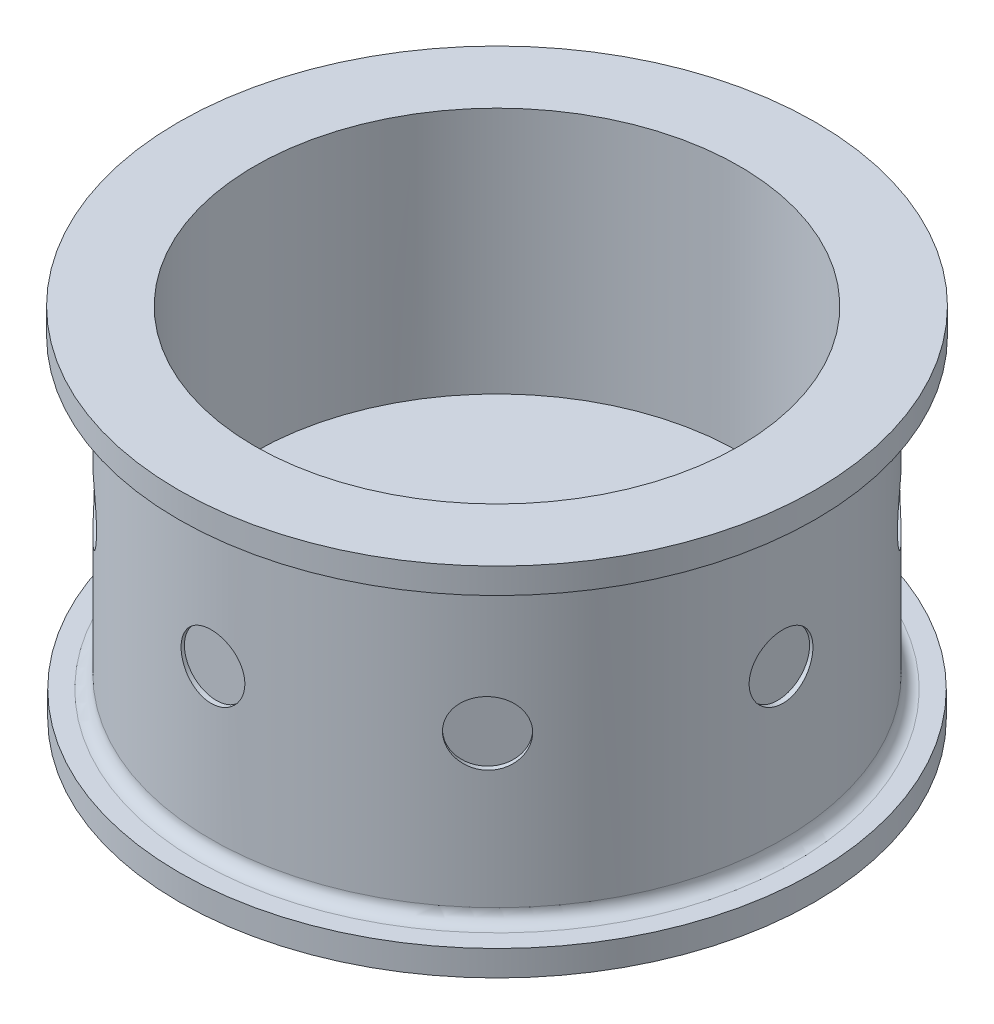
SolidWorks part; units mm, degrees
ref_plane "Alzado" through (0, 0, 0) normal (0, 0, 1) x (1, 0, 0)
ref_plane "Planta" through (0, 0, 0) normal (0, 1, 0) x (1, 0, 0)
ref_plane "Vista lateral" through (0, 0, 0) normal (1, 0, 0) x (0, 0, -1)
sketch "Sketch1" plane through (0, 0, 0) normal (0, 1, 0) x (1, 0, 0)
  circle A0 centre (0, 0) radius 19
  circle A1 centre (0, 0) radius 22.4
  dimension "D1" = 38
  dimension "D2" = 3.4
extrude "Boss-Extrude1" add sketch "Sketch1" along normal blind 28
sketch "Sketch2" plane through (0, 0, 0) normal (0, -1, 0) x (1, 0, 0)
  line L1 (-22.4, 0) -> (0, 0)
  line L2 (0, 0) -> (22.4, 0)
  arc A1 (-22.4, 0) -> (22.4, 0) centre (0, 0) ccw
  dimension "D1" = 22.4
extrude "Boss-Extrude2" add sketch "Sketch2" against normal blind 8.6
sketch "Sketch3" plane through (0, 0, 0) normal (0, -1, 0) x (-1, 0, 0)
  circle A0 centre (0, 0) radius 4
  dimension "D1" = 8
extrude "Cut-Extrude1" cut sketch "Sketch3" against normal blind 9
sketch "Sketch4" plane through (0, 0, 0) normal (0, -1, 0) x (-1, 0, 0)
  circle A0 centre (0, 0) radius 24.9
  circle A1 centre (0, 0) radius 22.4 construction
  circle A2 centre (0, 0) radius 22.3906
  dimension "D1" = 2.5
  dimension "D2" = 0
extrude "Boss-Extrude3" add sketch "Sketch4" against normal blind 2
sketch "Sketch5" plane through (0, 28, 0) normal (0, 1, 0) x (1, 0, 0)
  circle A0 centre (0, 0) radius 24.9643
  circle A1 centre (0, 0) radius 22.4
extrude "Boss-Extrude4" add sketch "Sketch5" against normal blind 2
fillet "Fillet1" radius 1 2 edges at (0, 26, 22.4) (0, 2, -22.4)
ref_plane "Plane4" through (0, 0, -25) normal (0, 0, 1) x (1, 0, 0)
ref_plane "Plane5" through (0, 0, 0) normal (1, 0, 0) x (0, 0, -1)
sketch "Sketch7" plane through (0, 0, -25) normal (0, 0, 1) x (1, 0, 0)
  line L0 (0, -15.4) -> (0, 15.4) construction
  line L2 (-22.4, 3) -> (22.4, 3) construction
  circle A0 centre (-9.5, 4.5) radius 1.585
  dimension "D1" = 3.17
  dimension "D2" = 9.5
  dimension "D3" = 1.5
extrude "Cut-Extrude2" cut sketch "Sketch7" along normal blind 32
mirror "Mirror1" about plane through (0, 0, 0) normal (1, 0, 0) of "Cut-Extrude2"
sketch "Sketch8" plane through (0, 0, -25) normal (0, 0, 1) x (1, 0, 0)
  circle A0 centre (0, 14.7325) radius 2.5
  dimension "D1" = 5
extrude "Cut-Extrude3" cut sketch "Sketch8" along normal blind 3
ref_plane "Plane6" through (0, 0, 0) normal (0, 0, 1) x (1, 0, 0)
mirror "Mirror2" about plane through (0, 0, 0) normal (0, 0, 1) of "Cut-Extrude3"
ref_plane "Plane7" through (25, 0, 0) normal (1, 0, 0) x (0, 0, -1)
sketch "Sketch9" plane through (25, 0, 0) normal (1, 0, 0) x (0, 0, -1)
  circle A0 centre (0, 14.7325) radius 2.5
  dimension "D1" = 5
extrude "Cut-Extrude4" cut sketch "Sketch9" against normal blind 3
mirror "Mirror3" about plane through (0, 0, 0) normal (1, 0, 0) of "Cut-Extrude4"
ref_plane "Plane8" through (0, 0, 0) normal (0.7071, 0, -0.7071) x (-0.7071, 0, -0.7071)
ref_plane "Plane9" through (17.6777, 0, -17.6777) normal (0.7071, 0, -0.7071) x (-0.7071, 0, -0.7071)
sketch "Sketch10" plane through (17.6777, 0, -17.6777) normal (0.7071, 0, -0.7071) x (-0.7071, 0, -0.7071)
  circle A0 centre (-0.5217, 14.8305) radius 2.5
  dimension "D1" = 5
extrude "Cut-Extrude5" cut sketch "Sketch10" against normal blind 3
mirror "Mirror4" about plane through (0, 0, 0) normal (0.7071, 0, -0.7071) of "Cut-Extrude5"
mirror "Mirror5" about plane through (0, 0, 0) normal (1, 0, 0) of "Cut-Extrude5"
mirror "Mirror6" about plane through (0, 0, 0) normal (1, 0, 0) of "Mirror4"
